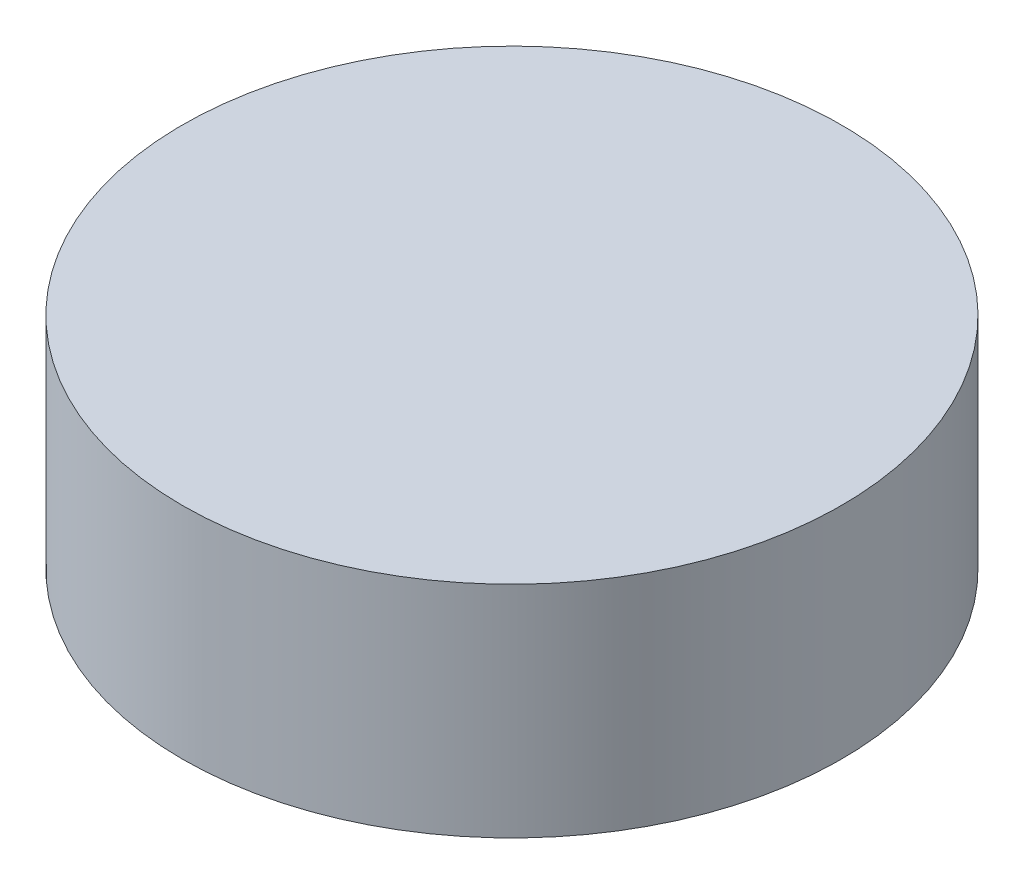
SolidWorks part; units mm, degrees
material "NdFeB（钕铁硼）"
ref_plane "前视基准面" through (0, 0, 0) normal (0, 0, 1) x (1, 0, 0)
ref_plane "上视基准面" through (0, 0, 0) normal (0, 1, 0) x (1, 0, 0)
ref_plane "右视基准面" through (0, 0, 0) normal (1, 0, 0) x (0, 0, -1)
sketch "草图1" plane through (0, 0, 0) normal (0, 1, 0) x (1, 0, 0)
  circle A0 centre (0, 0) radius 3
  dimension "D1" = 6
extrude "凸台-拉伸1" add sketch "草图1" along normal blind 2
